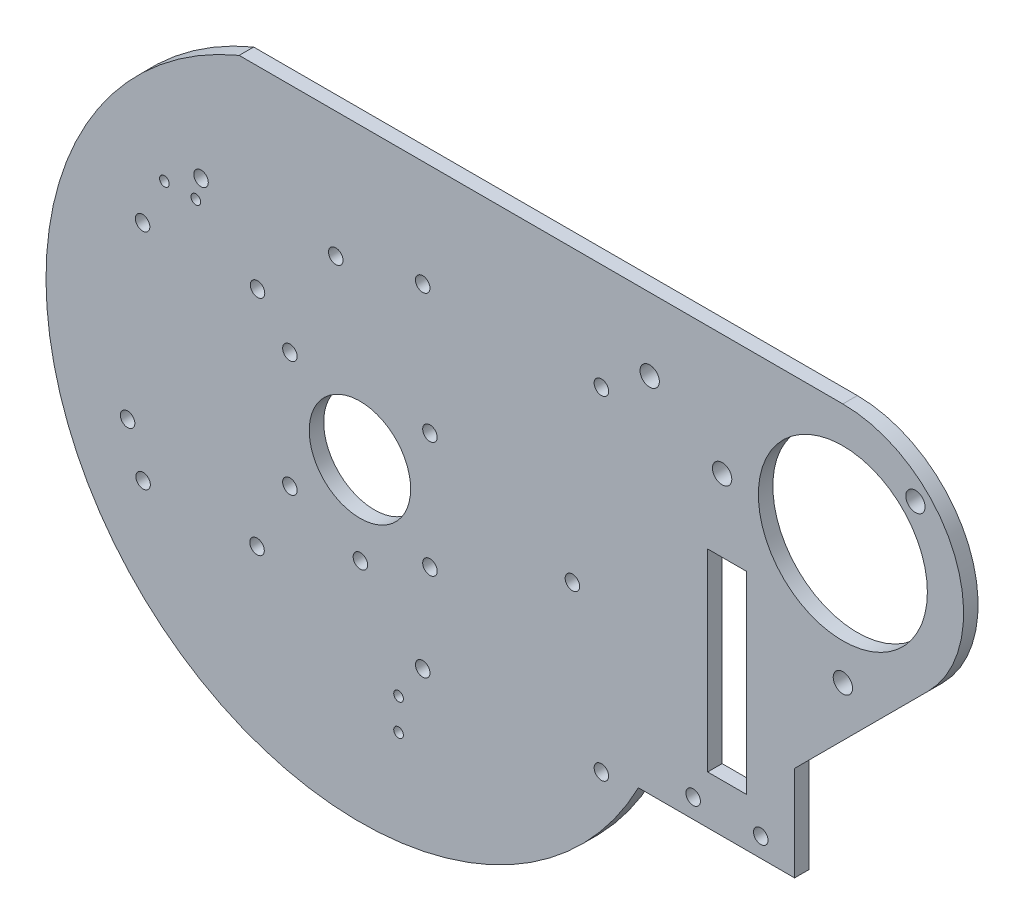
SolidWorks part; units mm, degrees
ref_plane "前视基准面" through (0, 0, 0) normal (0, 0, 1) x (1, 0, 0)
ref_plane "上视基准面" through (0, 0, 0) normal (0, 1, 0) x (1, 0, 0)
ref_plane "右视基准面" through (0, 0, 0) normal (1, 0, 0) x (0, 0, -1)
sketch "Sketch1" plane through (0, 0, 0) normal (0, 0, 1) x (1, 0, 0)
  line L0 (-10.9179, 60) -> (113.3582, 60) construction
  line L3 (-33.1662, 50) -> (-60, 50)
  line L4 (-60, 0) -> (-60, 50)
  line L6 (67.51, -32.8453) -> (81.2655, -19.0899) construction
  line L7 (90, -10.3553) -> (117.6777, 17.3223)
  line L12 (76, 7.9315) -> (76, -17.4174) construction
  line L13 (0, 60) -> (100, 60)
  line L15 (72, 20) -> (80, 20)
  line L16 (72, 20) -> (72, -20)
  line L17 (72, -20) -> (80, -20)
  line L18 (80, 20) -> (80, -20)
  line L19 (72, 20) -> (80, -20) construction
  line L20 (72, -20) -> (80, 20) construction
  line L23 (90, -30) -> (56.5685, -30)
  line L24 (90, -30) -> (90, -10.3553)
  line L25 (56.5685, -30) -> (51.9615, -30)
  line L26 (57.5608, -26) -> (84.9155, -26) construction
  arc A0 (0, 60) -> (51.9615, -30) centre (0, 0) ccw
  circle A2 centre (0, 0) radius 10.5
  arc A8 (117.6777, 17.3223) -> (100, 60) centre (100, 35) ccw
  circle A9 centre (100, 35) radius 17.5
  circle A10 centre (69, -26) radius 1.5
  circle A11 centre (83, -26) radius 1.5
  point P18 (76, 0)
  dimension "D1" = 120
  dimension "D2" = 136
  dimension "D3" = 21
  dimension "D5" = 50
  dimension "D4" = 100
  dimension "D6" = 35
  dimension "D13" = 7
  dimension "D7" = 10
  dimension "D8" = 8
  dimension "D9" = 40
  dimension "D10" = 90
  dimension "D11" = 150
  dimension "D12" = 6
extrude "Boss-Extrude1" add sketch "Sketch1" along normal blind 3
sketch "Sketch2" plane through (0, 0, 3) normal (0, 0, 1) x (1, 0, 0)
  line L1 (-60, 0) -> (-60, 50) construction
  line L2 (0, 60) -> (100, 60) construction
  circle A1 centre (0, 0) radius 57
  circle A2 centre (60, 45) radius 2
  circle A6 centre (100, 35) radius 14
  dimension "D1" = 15
  dimension "D5" = 28
  dimension "D2" = 120
extrude "Cut-Extrude1" cut sketch "Sketch2" against normal up to next
sketch "Sketch3" plane through (0, 0, 3) normal (0, 0, 1) x (1, 0, 0)
  line L0 (117.6777, 52.6777) -> (112.3744, 47.3744) construction
  circle A0 centre (100, 35) radius 17.5 construction
  circle A1 centre (100, 35) radius 25 construction
  circle A2 centre (100, 10) radius 2
  circle A3 centre (75, 35) radius 2
  circle A4 centre (115.026, 50.026) radius 2
  dimension "D1" = 35
extrude "Cut-Extrude2" cut sketch "Sketch3" against normal up to next
sketch "Sketch4" plane through (0, 0, 3) normal (0, 0, 1) x (1, 0, 0)
  circle A0 centre (0, 0) radius 60
  circle A1 centre (0, 0) radius 65
extrude "Boss-Extrude2" add sketch "Sketch4" against normal up to surface (3 mm away) up to face at (102, 10, 0)
sketch "Sketch5" plane through (0, 0, 3) normal (0, 0, 1) x (1, 0, 0)
  line L1 (-60, 50) -> (-41.5331, 50)
  line L2 (-60, 50) -> (-60, 25)
  arc A0 (-41.5331, 50) -> (-60, 25) centre (0, 0) ccw
extrude "Cut-Extrude3" cut sketch "Sketch5" against normal blind 10
sketch "Sketch6" plane through (0, 0, 3) normal (0, 0, 1) x (1, 0, 0)
  line L0 (25, 60) -> (-25, 60)
  arc A0 (25, 60) -> (57.6628, -30) centre (0, 0) ccw construction
  arc A1 (-25, 60) -> (25, 60) centre (0, 0) cw
extrude "Cut-Extrude4" cut sketch "Sketch6" against normal blind 10
sketch "Sketch7" plane through (0, 0, 3) normal (0, 0, 1) x (1, 0, 0)
  circle A0 centre (-14.5, 12) radius 1.5
  circle A1 centre (14.5, 12) radius 1.5
  circle A2 centre (-14.5, -12) radius 1.5
  circle A3 centre (14.5, -12) radius 1.5
extrude "Cut-Extrude5" cut sketch "Sketch7" against normal up to next
sketch "Sketch8" plane through (0, 0, 3) normal (0, 0, 1) x (1, 0, 0)
  line L0 (-25, 60) -> (100, 60) construction
  line L1 (90, -30) -> (90, -10.3553) construction
  circle A0 centre (50, 38) radius 1.5
  circle A1 centre (13, 38) radius 1.5
  circle A2 centre (50, -31) radius 1.5
  circle A3 centre (13, -31) radius 1.5
  circle A4 centre (-5, 34) radius 1.5
  circle A6 centre (-32.9, 34) radius 1.5
  circle A7 centre (0.1, -18.1) radius 1.5
  circle A8 centre (-48.1, -16.8) radius 1.5
  dimension "D1" = 22
  dimension "D2" = 40
  dimension "D3" = 37
  dimension "D4" = 69
  dimension "D6" = 26
  dimension "D8" = 27.9
  dimension "D9" = 5.1
  dimension "D11" = 15.2
  dimension "D12" = 1.3
  dimension "D5" = 69
  dimension "D7" = 95
  dimension "D10" = 50.8
extrude "Cut-Extrude6" cut sketch "Sketch8" against normal up to next
sketch "Sketch9" plane through (0, 0, 3) normal (0, 0, 1) x (1, 0, 0)
  line L0 (-25, 60) -> (100, 60) construction
  circle A1 centre (-21.3, -26.2) radius 1.5
  circle A4 centre (-21.2, 20) radius 1.5
  circle A6 centre (-45, 20) radius 1.5
  circle A7 centre (-44.9, -26.2) radius 1.5
  dimension "D1" = 40
  dimension "D2" = 46.2
  dimension "D3" = 23.8
  dimension "D4" = 0.1
  dimension "D5" = 23.6
  dimension "D6" = 20
extrude "Cut-Extrude7" cut sketch "Sketch9" against normal up to next
sketch "Sketch10" plane through (0, 0, 3) normal (0, 0, 1) x (1, 0, 0)
  point P0 (44, 0)
  dimension "D1" = 44
hole_wizard "Ø3.0mm Dowel Hole1" positions "Sketch11" profile "Sketch12" hole size "Ø3.0" standard "ANSI Metric"
sketch "Sketch11" plane through (0, 0, 3) normal (0, 0, 1) x (1, 0, 0)
  point P0 (44, 0)
sketch "Sketch12" plane through (44, 0, 3) normal (1, 0, 0) x (0, -1, 0)
  line L0 (0, 0) -> (0, 12.2013)
  line L1 (0, 12.2013) -> (1.5, 11.3)
  line L2 (1.5, 11.3) -> (1.5, 0)
  line L5 (1.5, 0) -> (0, 0)
  line L10 (0, 12.2013) -> (-1.5, 11.3) construction
  line L11 (0, -6.35) -> (0, 107.95) construction
  dimension "Hole Dia." = 3
  dimension "Hole Depth" = 11.3
  dimension "Drill Angle" = 118
sketch "Sketch13" plane through (0, 0, 3) normal (0, 0, 1) x (1, 0, 0)
  line L0 (0, 0) -> (0, -60) construction
  line L1 (0, 0) -> (-51.9615, 30) construction
  line L2 (8, -35.3) -> (8, -24.7118) construction
  line L3 (0, -27) -> (-6, -27)
  line L4 (0, -27) -> (0, -33)
  line L5 (0, -33) -> (-6, -33)
  line L6 (-6, -27) -> (-6, -33)
  line L7 (-23.3827, 13.5) -> (-28.5788, 16.5)
  line L8 (8, -35.3) -> (2, -35.3)
  line L9 (8, -35.3) -> (8, -37.4)
  line L10 (8, -48) -> (2, -48)
  line L11 (2, -35.3) -> (2, -48)
  line L12 (-28.5788, 16.5) -> (-25.5788, 21.6962)
  line L13 (-25.5788, 21.6962) -> (-20.3827, 18.6962)
  line L14 (-20.3827, 18.6962) -> (-23.3827, 13.5)
  line L15 (-25.5788, 21.6962) -> (-32.286, 21.6962) construction
  line L16 (-25.5788, 21.6962) -> (-25.5788, 27.9547) construction
  line L21 (-46.719, 29.6962) -> (-41.4788, 29.6962) construction
  line L22 (-43.5788, 39.7653) -> (-43.5788, 29.6962) construction
  line L23 (-43.5788, 29.6962) -> (-43.5788, 23.6962)
  line L24 (-43.5788, 23.6962) -> (-30.8788, 23.6962)
  line L25 (-30.8788, 23.6962) -> (-30.8788, 29.6962)
  line L26 (-30.8788, 29.6962) -> (-32.9788, 29.6962)
  line L27 (-37.2288, 29.6962) -> (-37.2288, 23.6962) construction
  line L28 (-39.4788, 29.6962) -> (-34.9788, 29.6962) construction
  line L29 (-41.4788, 29.6962) -> (-43.5788, 29.6962)
  line L30 (-34.9788, 29.6962) -> (-39.4788, 29.6962)
  line L31 (-32.9788, 29.6962) -> (-27.1092, 29.6962) construction
  line L32 (8, -39.4) -> (8, -43.9)
  line L33 (8, -45.9) -> (8, -48)
  circle A0 centre (8, -38.4) radius 1
  circle A1 centre (8, -44.9) radius 1
  circle A2 centre (-33.9788, 29.6962) radius 1
  circle A3 centre (-40.4788, 29.6962) radius 1
  point P8 (0, -30)
  point P20 (-25.9808, 15)
  dimension "D9" = 2
  dimension "D10" = 2
  dimension "D19" = 3.25
  dimension "D1" = 60
  dimension "D2" = 60
  dimension "D3" = 120
  dimension "D4" = 6
  dimension "D5" = 6
  dimension "D6" = 8
  dimension "D7" = 12.7
  dimension "D8" = 18
  dimension "D13" = 6
  dimension "D14" = 6
  dimension "D15" = 8
  dimension "D16" = 18
  dimension "D17" = 6
  dimension "D18" = 12.7
  dimension "D20" = 3.25
extrude "Cut-Extrude8" cut sketch "Sketch13" against normal up to next contours A3 | A2 | A0 | A1
